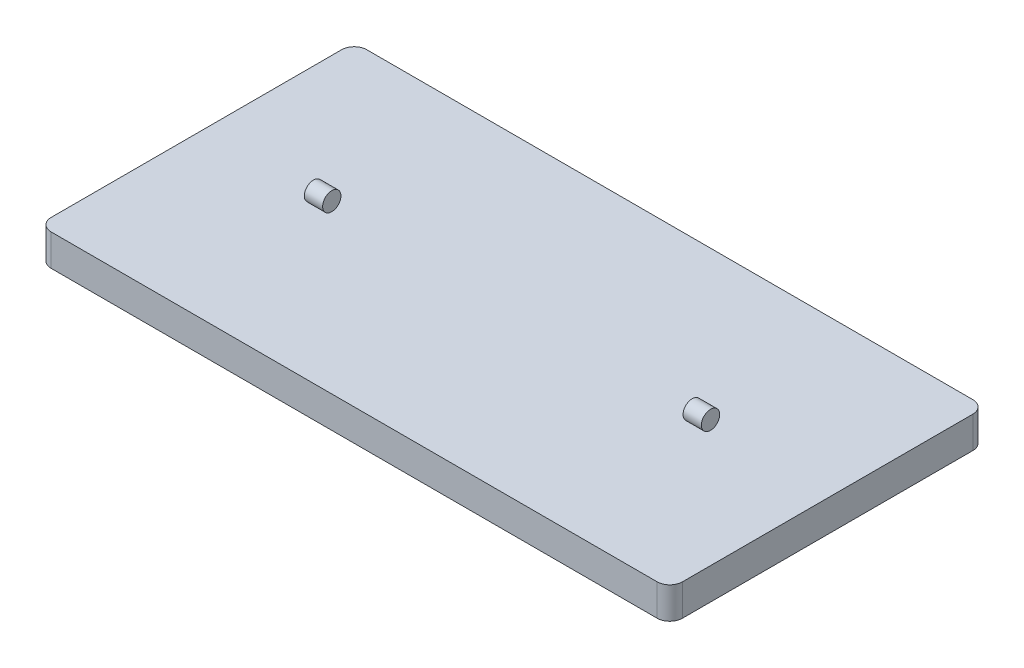
SolidWorks part; units mm, degrees
ref_plane "Front Plane" through (0, 0, 0) normal (0, 0, 1) x (1, 0, 0)
ref_plane "Top Plane" through (0, 0, 0) normal (0, 1, 0) x (1, 0, 0)
ref_plane "Right Plane" through (0, 0, 0) normal (1, 0, 0) x (0, 0, -1)
sketch "Sketch1" plane through (0, 0, 0) normal (0, 1, 0) x (1, 0, 0)
  line L1 (250, -125) -> (-250, -125)
  line L2 (250, -125) -> (250, 125)
  line L3 (250, 125) -> (-250, 125)
  line L4 (-250, -125) -> (-250, 125)
  line L5 (250, -125) -> (-250, 125) construction
  line L6 (250, 125) -> (-250, -125) construction
  point P0 (0, 0)
  dimension "D1" = 500
  dimension "D2" = 250
extrude "Boss-Extrude1" add sketch "Sketch1" along normal blind 25
fillet "Fillet1" radius 10 4 edges at (-250, 12.5, -125) (250, 12.5, -125) (250, 12.5, 125) (-250, 12.5, 125)
ref_plane "Plane1" through (150, 0, 0) normal (1, 0, 0) x (0, 0, -1)
sketch "Sketch5" plane through (150, 0, 0) normal (1, 0, 0) x (0, 0, -1)
  line L0 (-115, 25) -> (115, 25) construction
  circle A0 centre (0, 32.25) radius 7.25
  dimension "D1" = 14.5
extrude "Boss-Extrude2" add sketch "Sketch5" along normal blind 7.25 and the other way blind 7.25 separate body
mirror "Mirror3" about plane through (0, 0, 0) normal (1, 0, 0) of bodies 102
